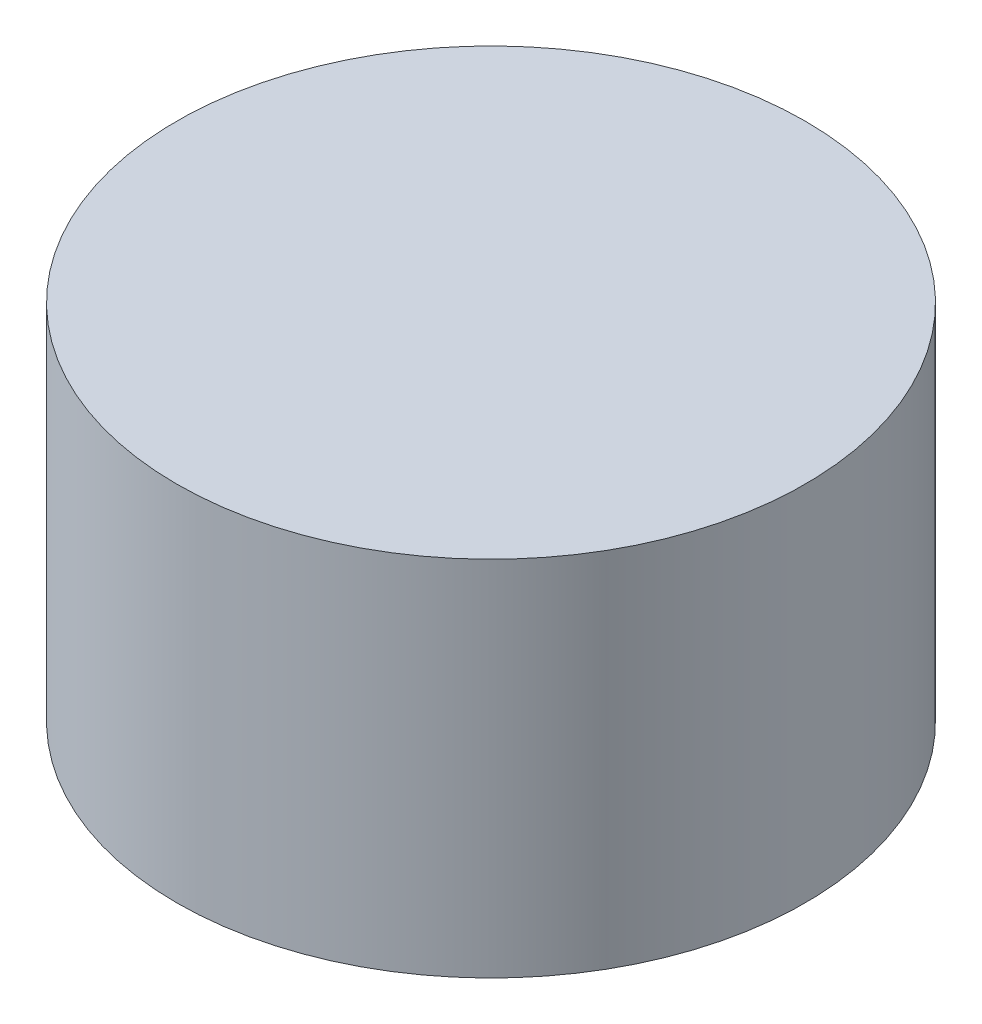
SolidWorks part; units mm, degrees
ref_plane "Front Plane" through (0, 0, 0) normal (0, 0, 1) x (1, 0, 0)
ref_plane "Top Plane" through (0, 0, 0) normal (0, 1, 0) x (1, 0, 0)
ref_plane "Right Plane" through (0, 0, 0) normal (1, 0, 0) x (0, 0, -1)
sketch "Sketch1" plane through (0, 0, 0) normal (0, 1, 0) x (1, 0, 0)
  circle A0 centre (0, 0) radius 260
  dimension "D1" = 520
extrude "Boss-Extrude1" add sketch "Sketch1" along normal blind 300 from offset 240
